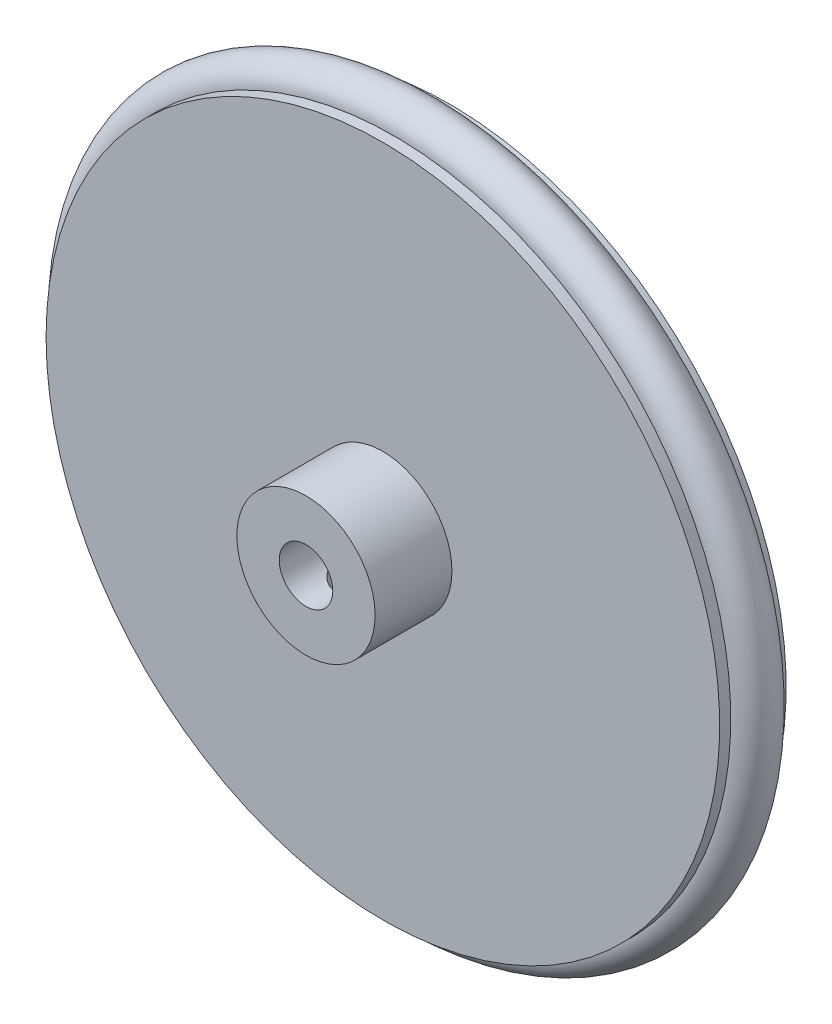
SolidWorks part; units mm, degrees
ref_plane "Front Plane" through (0, 0, 0) normal (0, 0, 1) x (1, 0, 0)
ref_plane "Top Plane" through (0, 0, 0) normal (0, 1, 0) x (1, 0, 0)
ref_plane "Right Plane" through (0, 0, 0) normal (1, 0, 0) x (0, 0, -1)
sketch "Sketch1" plane through (0, 0, 0) normal (0, 0, 1) x (1, 0, 0)
  circle A0 centre (0, 0) radius 39
  dimension "D1" = 78
extrude "Boss-Extrude1" add sketch "Sketch1" along normal mid plane 7.7
sketch "Sketch2" plane through (0, 0, 0) normal (0, 1, 0) x (1, 0, 0)
  line L0 (39, -3.85) -> (39, 3.85) construction
  line L1 (29, 0) -> (30.643, 0) construction
  circle A0 centre (39, 0) radius 2.5
  point P2 (39, 0)
  dimension "D1" = 5
sweep "Cut-Sweep1" cut profiles "Sketch2" path edge at (39, 0, -3.85)
sketch "Sketch4" plane through (0, 0, 3.85) normal (0, 0, 1) x (1, 0, 0)
  circle A0 centre (0, 0) radius 8
  dimension "D1" = 16
extrude "Boss-Extrude2" add sketch "Sketch4" along normal blind 8.9
sketch "Sketch5" plane through (0, 0, 12.75) normal (0, 0, 1) x (1, 0, 0)
  circle A0 centre (0, 0) radius 3.1
  dimension "D1" = 6.2
extrude "Cut-Extrude1" cut sketch "Sketch5" against normal offset from surface (15.6 mm away) 1 up to face at (39, 0, -3.85)
sketch "Sketch6" plane through (0, 0, 0) normal (0, 1, 0) x (1, 0, 0)
  line L0 (0, -4.235) -> (0, 4.235) construction
  line L1 (-8, -12.75) -> (8, -12.75) construction
  circle A0 centre (0, -7.5) radius 2
  dimension "D1" = 4
  dimension "D2" = 5.25
extrude "Cut-Extrude2" cut sketch "Sketch6" against normal through all
ref_axis "Axis1" through (0, 0, 12.75) along (0, 0, -1)
sketch "Sketch3" plane through (0, 0, 0) normal (0, 1, 0) x (1, 0, 0)
  line L0 (-42.9, 0) -> (42.9, 0) construction
  circle A0 centre (39, 0) radius 2.5612
  point P4 (39, 0)
revolve "Revolve1" add sketch "Sketch3" angle 360 about axis through (0, 0, 12.75) along (0, 0, -1)
